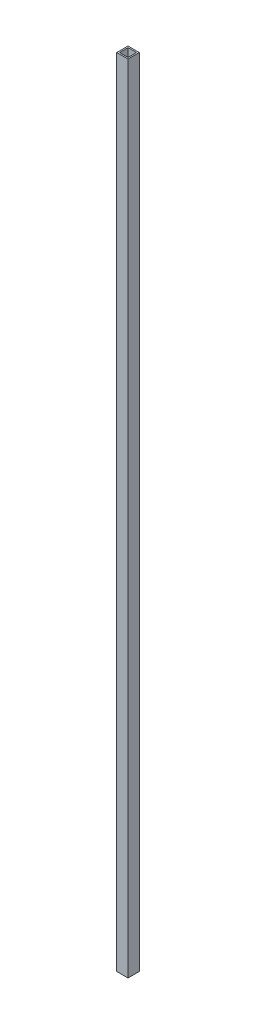
SolidWorks part; units mm, degrees
ref_plane "Piano frontale" through (0, 0, 0) normal (0, 0, 1) x (1, 0, 0)
ref_plane "Piano superiore" through (0, 0, 0) normal (0, 1, 0) x (1, 0, 0)
ref_plane "Piano destro" through (0, 0, 0) normal (1, 0, 0) x (0, 0, -1)
sketch "Schizzo1" plane through (0, 0, 0) normal (0, 1, 0) x (1, 0, 0)
  line L0 (15, 15) -> (-15, 15)
  line L1 (20, -20) -> (-20, -20)
  line L2 (20, -20) -> (20, 20)
  line L3 (20, 20) -> (-20, 20)
  line L4 (-20, -20) -> (-20, 20)
  line L5 (20, -20) -> (-20, 20) construction
  line L6 (20, 20) -> (-20, -20) construction
  line L7 (-15, -15) -> (-15, 15)
  line L8 (15, -15) -> (-15, -15)
  line L9 (15, -15) -> (15, 15)
  point P0 (0, 0)
  dimension "D1" = 40
  dimension "D2" = 40
  dimension "D3" = 5
extrude "Estrusione-Estrusione1" add sketch "Schizzo1" along normal blind 2817
